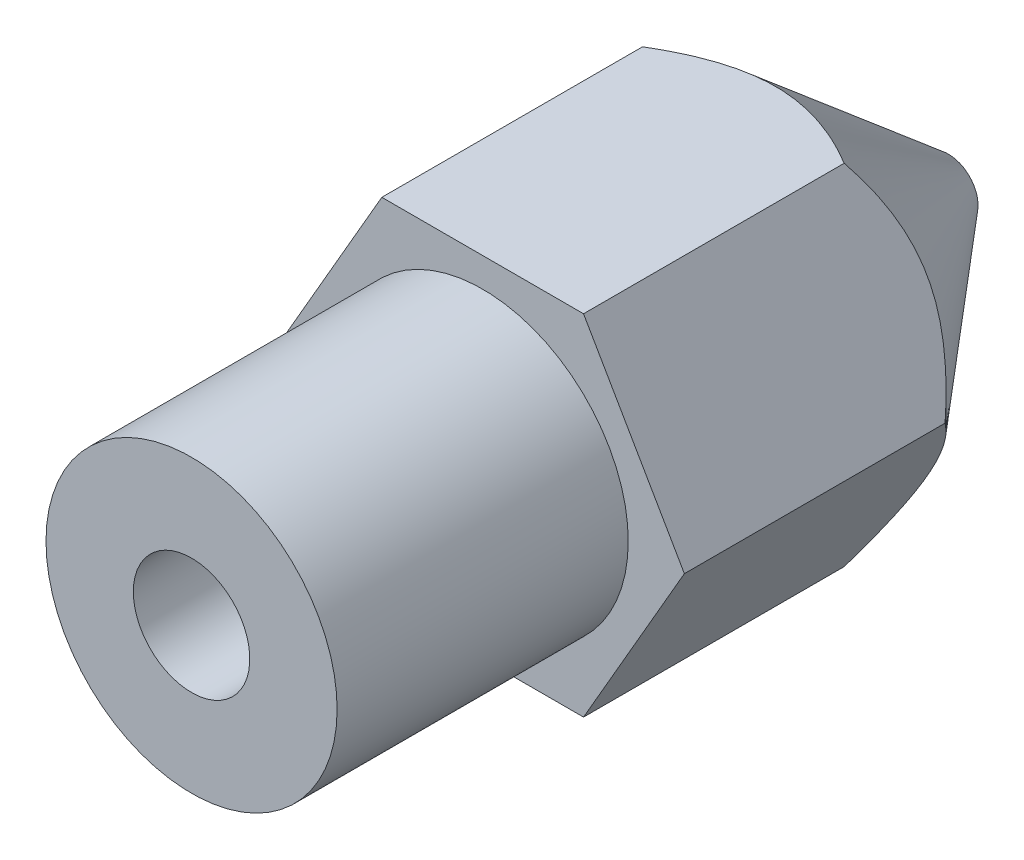
SolidWorks part; units mm, degrees
material "Brass"
ref_plane "Front Plane" through (0, 0, 0) normal (0, 0, 1) x (1, 0, 0)
ref_plane "Top Plane" through (0, 0, 0) normal (0, 1, 0) x (1, 0, 0)
ref_plane "Right Plane" through (0, 0, 0) normal (1, 0, 0) x (0, 0, -1)
sketch "Sketch1" plane through (0, 0, 0) normal (0, 0, 1) x (1, 0, 0)
  line L1 (1.7321, 3) -> (-1.7321, 3)
  line L2 (-1.7321, 3) -> (-3.4641, 0)
  line L3 (-3.4641, 0) -> (-1.7321, -3)
  line L4 (-1.7321, -3) -> (1.7321, -3)
  line L5 (1.7321, -3) -> (3.4641, 0)
  line L6 (3.4641, 0) -> (1.7321, 3)
  circle A0 centre (0, 0) radius 3 construction
  dimension "D1" = 6
extrude "Boss-Extrude1" add sketch "Sketch1" along normal blind 8
sketch "Sketch2" plane through (0, 0, 0) normal (0, 1, 0) x (1, 0, 0)
  line L0 (0, 0) -> (0, -8) construction
  line L1 (1.7321, -8) -> (-1.7321, -8) construction
  line L2 (-0.508, 0) -> (-3.4641, -3.5229)
  line L3 (1.7321, 0) -> (-1.7321, 0) construction
  line L4 (-3.4641, -8) -> (-3.4641, 0) construction
  line L5 (-3.4641, -3.5229) -> (-3.4641, 0)
  line L6 (-3.4641, 0) -> (-0.508, 0)
  dimension "D1" = 50
  dimension "D2" = 0.508
revolve "Cut-Revolve1" cut sketch "Sketch2" angle 360 about L0
sketch "Sketch3" plane through (0, 0, 8) normal (0, 0, 1) x (1, 0, 0)
  circle A0 centre (0, 0) radius 2.5
  dimension "D1" = 5
extrude "Boss-Extrude2" add sketch "Sketch3" along normal blind 5
sketch "Sketch4" plane through (0, 0, 0) normal (0, 1, 0) x (1, 0, 0)
  line L0 (0, 0) -> (0, -13)
  line L1 (-2.5, -13) -> (2.5, -13) construction
  line L2 (0, -13) -> (-1, -13)
  line L3 (-1, -13) -> (-1, -1.6383)
  line L4 (-1, -1.6383) -> (-0.2, -1.2129)
  line L5 (-0.2, -1.2129) -> (-0.2, 0)
  line L6 (0.508, 0) -> (-0.508, 0) construction
  line L7 (-0.2, 0) -> (0, 0)
  dimension "D1" = 0.2
  dimension "D2" = 1
  dimension "D3" = 118
  dimension "D4" = 1.2129
revolve "Cut-Revolve2" cut sketch "Sketch4" angle 360 about L0
